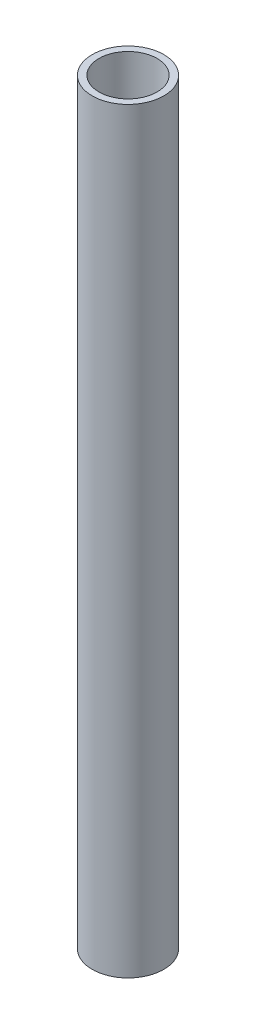
SolidWorks part; units mm, degrees
material "СТ3КП"
ref_plane "Спереди" through (0, 0, 0) normal (0, 0, 1) x (1, 0, 0)
ref_plane "Сверху" through (0, 0, 0) normal (0, 1, 0) x (1, 0, 0)
ref_plane "Справа" through (0, 0, 0) normal (1, 0, 0) x (0, 0, -1)
sketch "Эскиз1" plane through (0, 0, 0) normal (0, 1, 0) x (1, 0, 0)
  line L0 (0, 200839.2922) -> (0, -249082.8193) construction
  line L1 (-245, 9.15) -> (245, 9.15) construction
  circle B0 centre (0, -1.5) radius 8.65
  circle B1 centre (0, -1.5) radius 10.65
sketch_block_instance "Труба 21_3х2 1_2-1"
sketch_block "Труба 21_3х2 1_2" parameters "D2"=21.3, "D1"=2
extrude "Бобышка-Вытянуть1" add sketch "Эскиз1" along normal up to vertex (225 mm away)
